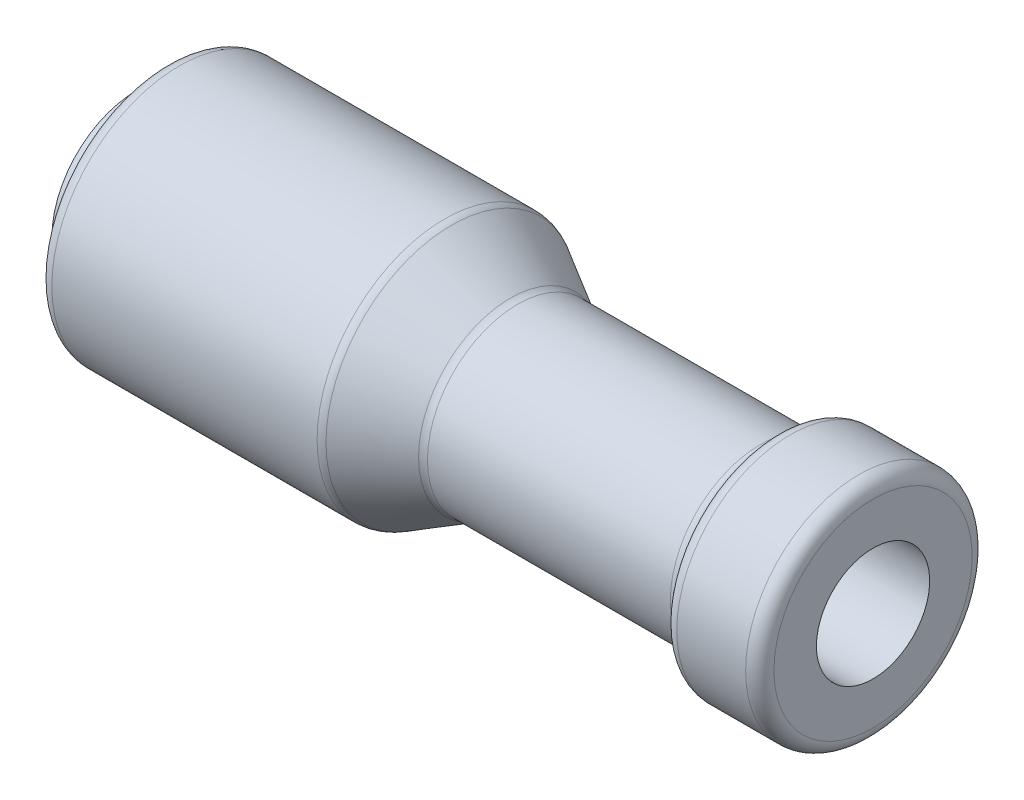
SolidWorks part; units mm, degrees
ref_plane "Спереди" through (0, 0, 0) normal (0, 0, 1) x (1, 0, 0)
ref_plane "Сверху" through (0, 0, 0) normal (0, 1, 0) x (1, 0, 0)
ref_plane "Справа" through (0, 0, 0) normal (1, 0, 0) x (0, 0, -1)
sketch "Эскиз1" plane through (0, 0, 0) normal (0, 1, 0) x (1, 0, 0)
  line L0 (-48.6811, 0) -> (40.4571, 0) construction
  line L1 (-20.3166, 2) -> (-20.3166, 3)
  line L2 (-20.3166, 3) -> (-19.3166, 3)
  line L3 (-19.3166, 3) -> (-19.3166, 4.5)
  line L4 (-19.3166, 4.5) -> (-9.3166, 4.5)
  line L5 (-9.3166, 4.5) -> (-7.0053, 3.1805)
  line L6 (-7.0053, 3.1805) -> (1.9947, 3.1805)
  line L7 (1.9947, 3.1805) -> (2.4626, 4)
  line L8 (2.4626, 4) -> (5.6834, 4)
  line L9 (5.6834, 4) -> (5.6834, 2)
  line L10 (-20.3166, 2) -> (5.6834, 2)
  dimension "D1" = 2
  dimension "D2" = 26
  dimension "D3" = 1
  dimension "D4" = 10
  dimension "D6" = 4.5
  dimension "D7" = 3.1805
  dimension "D8" = 9
revolve "Повернуть1" add sketch "Эскиз1" angle 360 about L0
fillet "Скругление1" radius 0.5 6 edges at (5.6834, 0, 4) (2.4626, 0, 4) (1.9947, 0, 3.1805) (-7.0053, 0, 3.1805) (-9.3166, 0, 4.5) (-19.3166, 0, 4.5)
